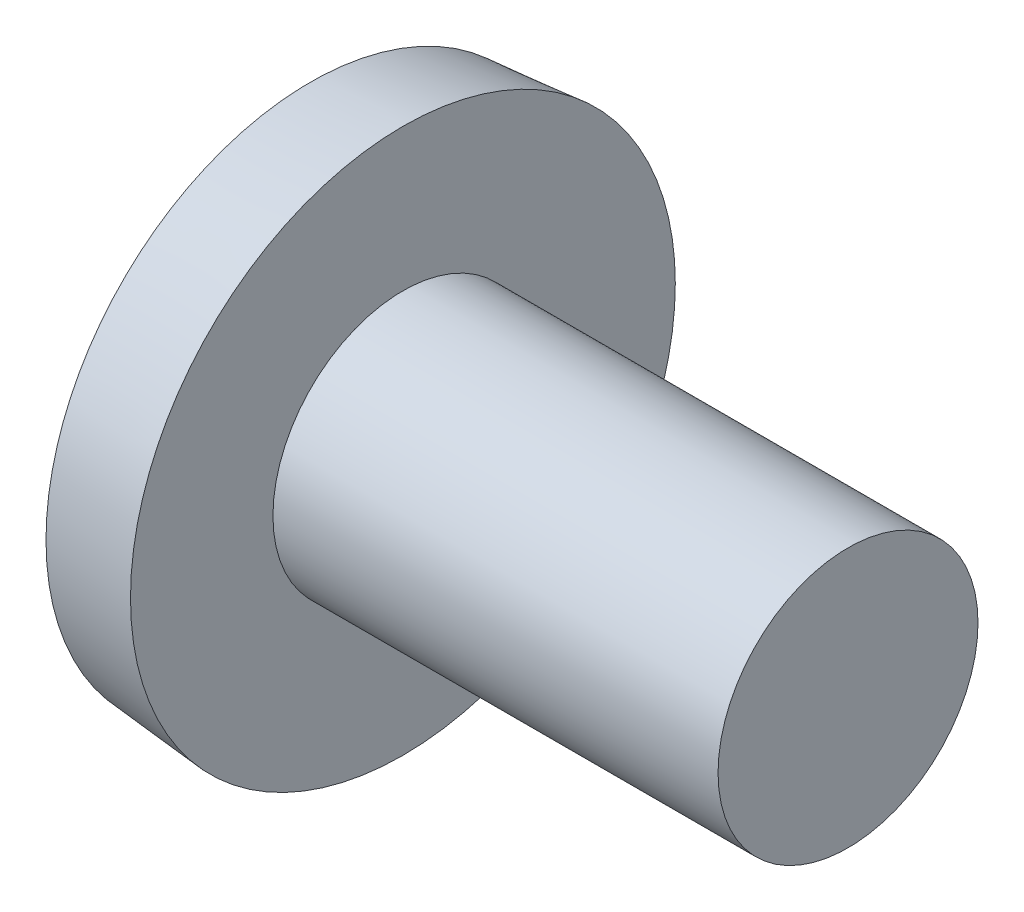
SolidWorks part; units mm, degrees
ref_plane "Plane1" through (0, 0, 0) normal (0, 0, 1) x (1, 0, 0)
ref_plane "Plane2" through (0, 0, 0) normal (0, 1, 0) x (1, 0, 0)
ref_plane "Plane3" through (0, 0, 0) normal (1, 0, 0) x (0, 0, -1)
sketch "BodySke" plane through (0, 0, 0) normal (0, 0, 1) x (1, 0, 0)
  line L0 (1.0414, 0.9271) -> (1.0414, 1.9431)
  line L1 (1.0414, 1.9431) -> (0.381, 1.8853)
  line L2 (-25.4, 0) -> (127, 0) construction
  line L3 (1.0414, -1.9431) -> (0.381, -1.8853) construction
  line L4 (1.0414, 0.9271) -> (4.2164, 0.9271)
  line L5 (4.2164, 0.9271) -> (4.2164, 0)
  line L6 (4.2164, 0) -> (0, 0)
  line L7 (1.0414, -0.9271) -> (4.2164, -0.9271) construction
  line L8 (1.3945, 6.35) -> (1.3945, -3.175) construction
  line L9 (1.0414, 6.35) -> (1.0414, -3.175) construction
  arc A0 (0, 0) -> (0.381, 1.8853) centre (4.8551, 0) cw
  dimension "Head_ang" = 85
  dimension "Oval_ht" = 0.381
  dimension "Head_ht" = 1.0414
  dimension "Diameter" = 1.8542
  dimension "Length" = 3.175
  dimension "Head_dia" = 3.8862
  dimension "Advance" = 0.3531
  dimension "Thread_nom" = 3.175
revolve "Base-Revolve" add sketch "BodySke" angle 360 about L2
cosmetic thread "ThreadCosmetic" [suppressed] parameters "Thread_length"=2.8219, "Thread_minor"=1.4351
sketch "Sketch2" plane through (0, 0, 0) normal (1, 0, 0) x (0, 0, -1)
  line L0 (1.9431, -0.3302) -> (1.9431, 0.3302)
  line L1 (1.9431, 0.3302) -> (-1.9431, 0.3302)
  line L2 (-1.9431, 0.3302) -> (-1.9431, -0.3302)
  line L3 (-1.9431, -0.3302) -> (1.9431, -0.3302)
  dimension "D1" = 3.8862
  dimension "D2" = 1.9431
  dimension "D3" = 0.3302
  dimension "Slot_width" = 0.6604
extrude "Slot" [suppressed] cut sketch "Sketch2" along normal blind 0.6096
sketch "Sketch3" plane through (0, 0, 0) normal (1, 0, 0) x (0, 0, -1)
  line L0 (-0.3175, 1.2319) -> (0.3175, 1.2319)
  line L1 (0.3175, 1.2319) -> (0.3175, -1.2319)
  line L2 (0.3175, -1.2319) -> (-0.3175, -1.2319)
  line L3 (-0.3175, -1.2319) -> (-0.3175, 1.2319)
  dimension "Cross_width" = 0.635
  dimension "D1" = 0.3175
  dimension "Cross_dia" = 2.4638
  dimension "D2" = 1.2319
ref_plane "Plane4" through (1.2954, 0, 0) normal (1, 0, 0) x (0, 0, -1)
sketch "Sketch4" plane through (1.2954, 0, 0) normal (1, 0, 0) x (0, 0, -1)
  line L0 (-0.1588, 0.1588) -> (0.1588, 0.1588)
  line L1 (0.1588, 0.1588) -> (0.1588, -0.1588)
  line L2 (0.1588, -0.1588) -> (-0.1587, -0.1588)
  line L3 (-0.1587, -0.1588) -> (-0.1588, 0.1588)
  dimension "D1" = 0.3175
  dimension "D2" = 0.1588
  dimension "D3" = 0.3175
  dimension "D4" = 0.1588
loft "Cross" cut profiles "Sketch3", "Sketch4"
pattern_circular "CirPattern1" count 2 every 90 about axis through (0, 0, 0) along (1, 0, 0) of "Cross"
sketch "ThdSchSke" plane through (0, 0, 0) normal (0, 0, 1) x (1, 0, 0)
  line L0 (1.3945, -0.7175) -> (1.2477, -0.9271)
  line L1 (1.3945, -0.7175) -> (1.5412, -0.9271)
  line L2 (1.5412, -0.9271) -> (1.5412, -1.1589)
  line L3 (-3.175, 0) -> (5.1513, 0) construction
  line L5 (1.5412, -1.1589) -> (1.2477, -1.1589)
  line L6 (1.2477, -1.1589) -> (1.2477, -0.9271)
  dimension "Diameter" = 1.8542
  dimension "SideAngle" = 55
  dimension "VeeAngle" = 70
  dimension "Thread_minor" = 1.4351
  dimension "Overcut" = 2.3177
  dimension "Start" = 1.3945
revolve "ThreadSchematic" [suppressed] cut sketch "ThdSchSke" angle 360 about L3
pattern_linear "ThdSchPat" [suppressed]
equation "\"D1@Sketch3\" = \"Cross_width@Sketch3\" / 2"
equation "\"D2@Sketch3\" = \"Cross_dia@Sketch3\" / 2"
equation "\"D1@Sketch4\" = \"Cross_width@Sketch3\"*.5"
equation "\"D2@Sketch4\" = \"D1@Sketch4\" / 2"
equation "\"D3@Sketch4\" = \"D1@Sketch4\""
equation "\"D4@Sketch4\" = \"D2@Sketch4\""
equation "\"D1@Sketch2\" = \"Head_dia@BodySke\""
equation "\"D2@Sketch2\" = \"D1@Sketch2\" / 2"
equation "\"D3@Sketch2\" = \"Slot_width@Sketch2\" / 2"
equation "\"Thread_length@ThreadCosmetic\" = ((sgn( (\"Length@BodySke\" - \"Advance@BodySke\" ) - \"Thread_nom@BodySke\" )-1)*( (\"Length@BodySke\" - \"Advance@BodySke\" ) - \"Thread_nom@BodySke\" ))/-2+ \"Thread_nom@BodySke\""
equation "\"Thread_minor@ThdSchSke\" = \"Thread_minor@ThreadCosmetic\""
equation "\"Diameter@ThdSchSke\" = \"Diameter@BodySke\""
equation "\"Overcut@ThdSchSke\" = \"Diameter@BodySke\" * 1.25"
equation "\"Start@ThdSchSke\" = \"Head_ht@BodySke\" + \"Length@BodySke\" - \"Thread_length@ThreadCosmetic\"  '---Non-countersunk---"
equation "\"Num_threads@ThdSchPat\" = int( \"Thread_length@ThreadCosmetic\" / \"Advance@BodySke\" + 0.999 )  + 1"
equation "\"Advance@ThdSchPat\" = \"Thread_length@ThreadCosmetic\" /  (\"Num_threads@ThdSchPat\" - 1) 'relax it"
